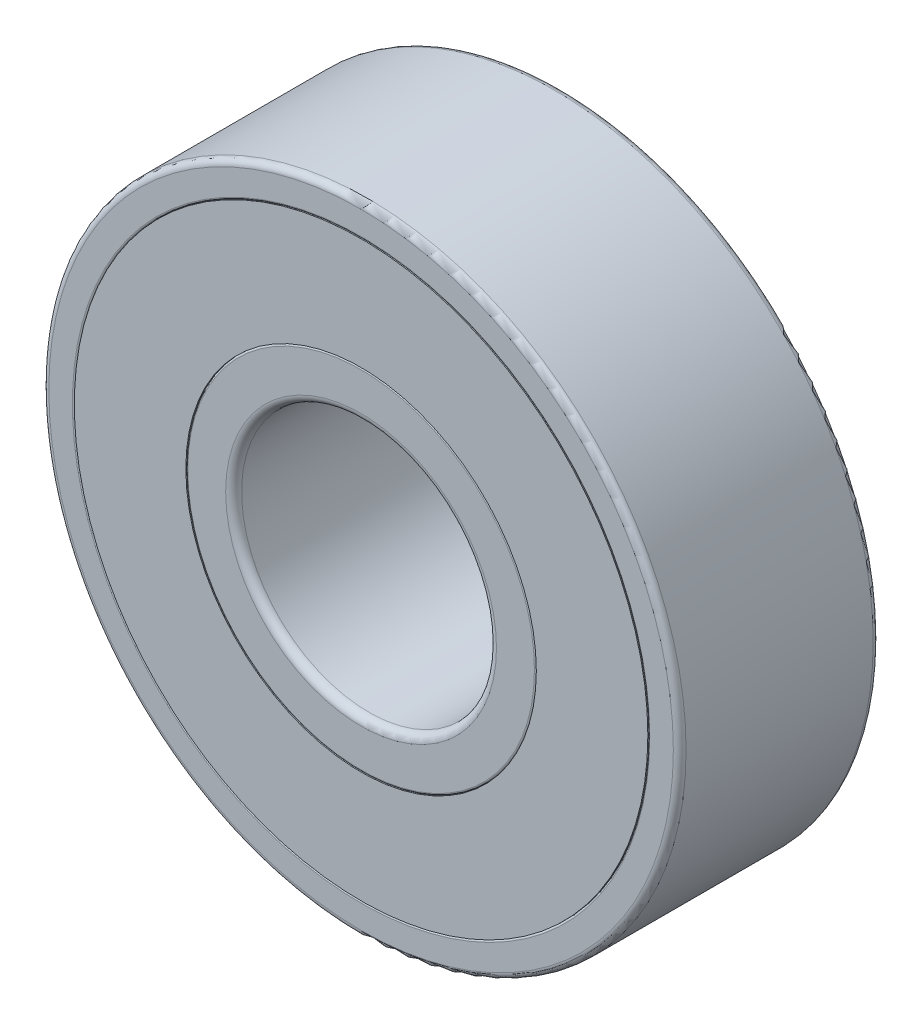
SolidWorks part; units mm, degrees
ref_plane "Front Plane" through (0, 0, 0) normal (0, 0, 1) x (1, 0, 0)
ref_plane "Top Plane" through (0, 0, 0) normal (0, 1, 0) x (1, 0, 0)
ref_plane "Right Plane" through (0, 0, 0) normal (1, 0, 0) x (0, 0, -1)
sketch "Sketch1" plane through (0, 0, 0) normal (0, 0, 1) x (1, 0, 0)
  line L0 (0, 5.5563) -> (0, 7.9375) construction
  line L1 (0, 3.175) -> (0, 5.5563) construction
  line L2 (0, 7.9375) -> (0, 7.1438) construction
  line L3 (0, 7.1438) -> (0, 6.35) construction
  line L4 (0, 6.35) -> (0, 5.5563) construction
  circle A0 centre (0, 0) radius 3.175
  circle A1 centre (0, 0) radius 7.9375
  circle A2 centre (0, 0) radius 7.1438 construction
  circle A4 centre (0, 0) radius 4.3656 construction
  point P6 (0, 4.3656)
  dimension "OD" = 15.875
  dimension "ID" = 6.35
sketch "Sketch2" plane through (0, 0, 0) normal (1, 0, 0) x (0, 0, -1)
  line L0 (-2.4892, -7.9375) -> (2.4892, -7.9375) construction
  point P2 (0, -7.9375)
  dimension "Width" = 4.9784
sketch "Sketch3" plane through (0, 0, 0) normal (1, 0, 0) x (0, 0, -1)
  line L0 (-2.4892, -7.9375) -> (2.4892, -7.9375)
  line L1 (2.4892, -7.9375) -> (2.4892, -7.1437)
  line L2 (2.4892, -7.1437) -> (-2.4892, -7.1438)
  line L3 (-2.4892, -7.1438) -> (-2.4892, -7.9375)
  line L6 (-2.4892, -3.175) -> (2.4892, -3.175)
  line L9 (-2.4892, -4.3656) -> (2.4892, -4.3656)
  line L12 (-2.4892, -4.3656) -> (-2.4892, -3.175)
  line L13 (2.4892, -4.3656) -> (2.4892, -3.175)
  line L14 (-2.4892, 0) -> (2.4892, 0) construction
  point P6 (0, -7.1438)
  point P7 (0, -4.3656)
  point P8 (0, -3.175)
  dimension "D1" = 2.7781
revolve "Revolve1" add sketch "Sketch3" angle 360 about L14
sketch "Sketch4" plane through (0, 0, 0) normal (1, 0, 0) x (0, 0, -1)
  line L0 (0, 7.9375) -> (0, -7.9375) construction
  line L1 (-2.4892, -4.3656) -> (-2.4892, -7.1438) construction
  circle A0 centre (0, -5.7547) radius 1.6669
  point P8 (-2.4892, -5.7547)
  dimension "D1" = 3.3337
revolve "Cut-Revolve1" cut sketch "Sketch4" angle 360 about L14
sketch "Sketch5" plane through (0, 0, 0) normal (1, 0, 0) x (0, 0, -1)
  line L0 (0, -4.0878) -> (0, -7.4216)
  line L1 (0, 7.9375) -> (0, -7.9375) construction
  circle A0 centre (0, -5.7547) radius 1.6669 construction
  arc A1 (0, -4.0878) -> (0, -7.4216) centre (0, -5.7547) cw
revolve "Revolve2" add sketch "Sketch5" angle 360 about L0
pattern_circular "CirPattern1" count 7 over 360 about axis through (0, 0, 0) along (0, 0, 1) of bodies 138
fillet "Fillet1" radius 0.1588 2 edges at (7.9375, 0, -2.4892) (7.9375, 0, 2.4892)
fillet "Fillet2" radius 0.1984 2 edges at (3.175, 0, -2.4892) (3.175, 0, 2.4892)
fillet "Fillet3" radius 0.0476 2 edges at (7.1437, 0, -2.4892) (7.1438, 0, 2.4892)
fillet "Fillet4" radius 0.0476 2 edges at (4.3656, 0, -2.4892) (4.3656, 0, 2.4892)
sketch "Sketch6" plane through (0, 0, 0) normal (0, 0, 1) x (1, 0, 0)
  circle A0 centre (0, 0) radius 7.1438 construction
  circle A1 centre (0, 0) radius 7.1438
  circle A2 centre (0, 0) radius 4.3656 construction
  circle A3 centre (0, 0) radius 4.3656
extrude "Boss-Extrude2" add sketch "Sketch6" along normal mid plane 4.9784 separate body
equation "\"D1@Sketch4\"=\"D1@Sketch3\"*1.2"
equation "\"D1@Fillet1\"=\"OD@Sketch1\"*0.01"
equation "\"D1@Fillet2\"=\"D1@Fillet1\"*1.25"
equation "\"D1@Fillet3\"=\"D1@Fillet1\"*0.3"
equation "\"D1@Fillet4\"=\"D1@Fillet3\""
equation "\"D1@Boss-Extrude2\"=\"width@sketch2\""
